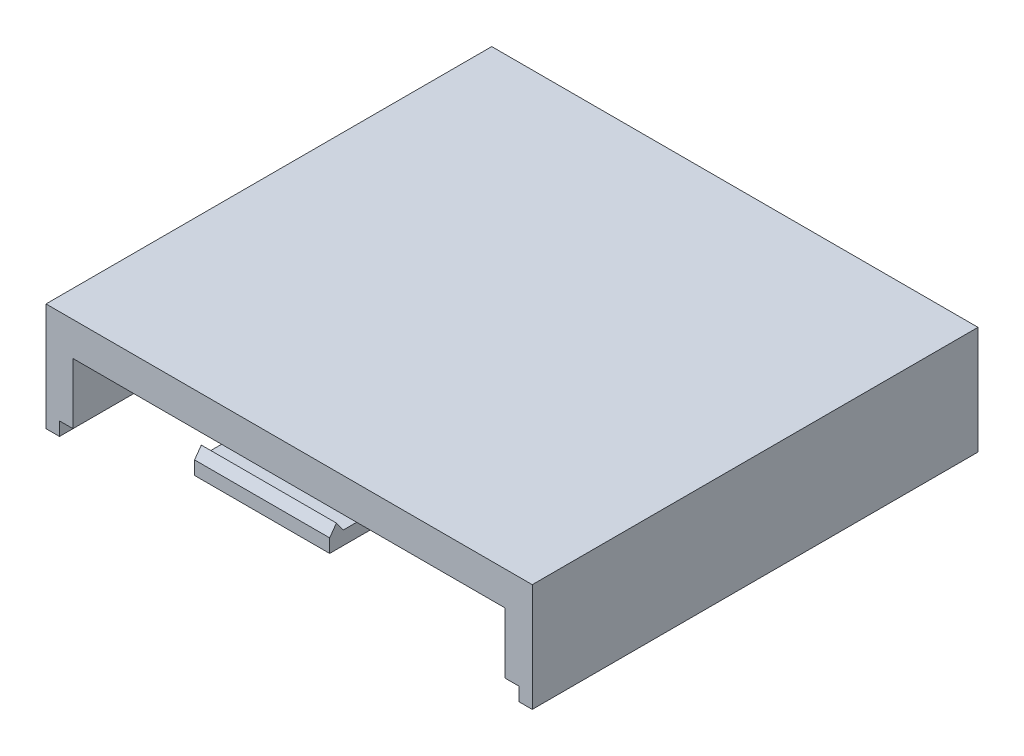
SolidWorks part; units mm, degrees
ref_plane "Alzado" through (0, 0, 0) normal (0, 0, 1) x (1, 0, 0)
ref_plane "Planta" through (0, 0, 0) normal (0, 1, 0) x (1, 0, 0)
ref_plane "Vista lateral" through (0, 0, 0) normal (1, 0, 0) x (0, 0, -1)
sketch "Croquis1" plane through (0, 0, 0) normal (0, 0, 1) x (1, 0, 0)
  line L0 (-18, -5.5) -> (-17, -5.5)
  line L1 (-17, -5.5) -> (-17, -4.5)
  line L2 (-17, -4.5) -> (-16, -4.5)
  line L3 (-16, -4.5) -> (-16, 0)
  line L4 (-16, 0) -> (16, 0)
  line L5 (16, 0) -> (16, -4.5)
  line L6 (16, -4.5) -> (17, -4.5)
  line L7 (17, -4.5) -> (17, -5.5)
  line L8 (17, -5.5) -> (18, -5.5)
  line L9 (18, -5.5) -> (18, 2.5)
  line L10 (18, 2.5) -> (-18, 2.5)
  line L11 (-18, 2.5) -> (-18, -5.5)
  point P10 (0, 2.5)
  dimension "D1" = 8
  dimension "D2" = 1
  dimension "D3" = 1
  dimension "D4" = 1
  dimension "D5" = 1
  dimension "D6" = 1
  dimension "D7" = 1
  dimension "D8" = 36
  dimension "D9" = 2.5
extrude "Saliente-Extruir1" add sketch "Croquis1" along normal blind 33
sketch "Croquis2" plane through (0, 0, 0) normal (0, 0, 1) x (1, 0, 0)
  line L0 (17, -5.5) -> (-17, -5.5)
  line L1 (-17, -5.5) -> (-17, -4.5)
  line L2 (-17, -4.5) -> (-16, -4.5)
  line L3 (-16, -4.5) -> (-16, 0)
  line L4 (-16, 0) -> (16, 0)
  line L5 (16, 0) -> (16, -4.5)
  line L6 (16, -4.5) -> (17, -4.5)
  line L7 (17, -4.5) -> (17, -5.5)
extrude "Saliente-Extruir2" add sketch "Croquis2" along normal blind 1.2
sketch "Croquis3" plane through (0, 0, 0) normal (0, 0, 1) x (1, 0, 0)
  line L0 (5, -5.5) -> (5, -10.5)
  line L1 (-18, -5.5) -> (18, -5.5) construction
  line L2 (5, -10.5) -> (-5, -10.5)
  line L3 (-5, -10.5) -> (-5, -5.5)
  line L4 (-5, -5.5) -> (-3.5, -5.5)
  line L5 (-3.5, -5.5) -> (-3.5, -8.55)
  line L6 (-3.5, -8.55) -> (3.5, -8.55)
  line L7 (3.5, -8.55) -> (3.5, -5.5)
  line L8 (3.5, -5.5) -> (5, -5.5)
  point P9 (0, -10.5)
  point P11 (0, -8.55)
  dimension "D1" = 10
  dimension "D2" = 7
  dimension "D3" = 5
  dimension "D4" = 1.95
extrude "Saliente-Extruir3" add sketch "Croquis3" along normal blind 1.2
sketch "Croquis4" plane through (0, 0, 33) normal (0, 0, 1) x (1, 0, 0)
  line L0 (-5, 0) -> (5, 0)
  line L1 (16, 0) -> (-16, 0) construction
  line L2 (5, 0) -> (5, -1)
  line L3 (5, -1) -> (-5, -1)
  line L4 (-5, -1) -> (-5, 0)
  point P6 (0, -1)
  dimension "D1" = 10
  dimension "D2" = 1
extrude "Saliente-Extruir4" add sketch "Croquis4" along normal blind 2 and the other way blind 1
sketch "Croquis5" plane through (5, 0, 0) normal (1, 0, 0) x (0, 0, -1)
  line L0 (-35, 0) -> (-34.5, 0.7)
  line L1 (-34.5, 0.7) -> (-34, 0)
  line L2 (-33, 0) -> (-35, 0) construction
  line L3 (-34, 0) -> (-35, 0)
  point P8 (-34.5, 0)
  dimension "D1" = 0.7
extrude "Saliente-Extruir5" add sketch "Croquis5" against normal up to surface (10 mm away) up to face at (-5, -0.4, 33.4)
